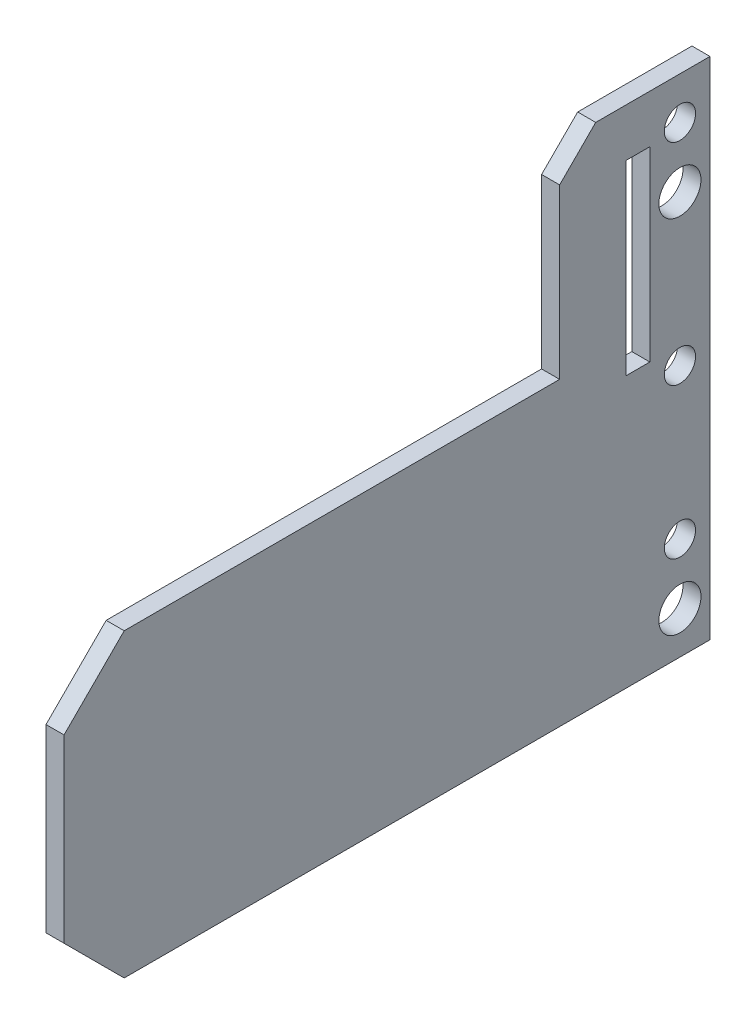
SolidWorks part; units mm, degrees
material "Alliage 1060"
ref_plane "Plan de face" through (0, 0, 0) normal (0, 0, 1) x (1, 0, 0)
ref_plane "Plan de dessus" through (0, 0, 0) normal (0, 1, 0) x (1, 0, 0)
ref_plane "Plan de droite" through (0, 0, 0) normal (1, 0, 0) x (0, 0, -1)
sketch "Esquisse1" plane through (0, 0, 0) normal (1, 0, 0) x (0, 0, -1)
  line L1 (2.5, 21) -> (-51.2, 21)
  line L2 (2.5, 21) -> (2.5, -21)
  line L3 (2.5, -21) -> (-51.2, -21)
  line L4 (-51.2, 21) -> (-51.2, -21)
  line L5 (-6.2, -1.4447) -> (-6.2, -2.9447) construction
  circle A2 centre (0, -17.5) radius 1.75
  circle A3 centre (0, 12.5) radius 1.75
  circle A4 centre (0, 12.5) radius 1.5 construction
  circle A5 centre (0, -17.5) radius 1.5 construction
  dimension "D2" = 3.5
  dimension "D1" = 45
extrude "Extrusion1" add sketch "Esquisse1" along normal blind 1.5
hole_wizard "Fraisage pour vis à tête fraisée M2.51" positions "Esquisse4" profile "Esquisse3" hole size "#0000" standard "Ansi Pouces" end condition through all
sketch "Esquisse4" plane through (1.5, 0, 0) normal (1, 0, 0) x (0, 0, -1)
  circle A0 centre (0, -17.5) radius 1.5 construction
  circle A1 centre (0, 12.5) radius 1.5 construction
  point P0 (0, 17.5)
  point P1 (0, -12.5)
  point P5 (0, 0)
  dimension "D2" = 5
  dimension "D1" = 5
sketch "Esquisse3" plane through (1.5, 17.5, 0) normal (0, 1, 0) x (0, 0, -1)
  line L0 (0, 0) -> (0, 1.5)
  line L1 (0, 1.5) -> (1.3, 1.5)
  line L2 (1.3, 1.5) -> (1.3, 0)
  line L5 (1.3, 0) -> (0, 0)
  line L11 (0, -6.35) -> (0, 107.95) construction
  dimension "Diamètre du perçage jusqu'au prochain" = 2.6
  dimension "Profondeur du perçage jusqu'au prochain" = 1.5
sketch "Esquisse5" plane through (0, 0, 0) normal (-1, 0, 0) x (0, 0, 1)
  line L0 (2.5, -21) -> (2.5, 21) construction
  line L1 (2.5, 17) -> (4.5, 17)
  line L2 (2.5, 17) -> (2.5, 1.5)
  line L3 (2.5, 1.5) -> (4.5, 1.5)
  line L4 (4.5, 17) -> (4.5, 1.5)
  dimension "D1" = 2
  dimension "D2" = 17
  dimension "D3" = 1.5
extrude "Enlèv. mat.-Extru.1" cut sketch "Esquisse5" against normal through all
sketch "Esquisse6" plane through (1.5, 0, 0) normal (1, 0, 0) x (0, 0, -1)
  line L0 (-51.2, 21) -> (-51.2, -1)
  line L1 (-51.2, 21) -> (-51.2, -21) construction
  line L2 (-46.2, 4) -> (-10, 4)
  line L3 (-10, 4) -> (-10, 18)
  line L4 (-10, 18) -> (-7, 21)
  line L5 (2.5, 21) -> (-51.2, 21) construction
  line L6 (-7, 21) -> (-51.2, 21)
  line L7 (-51.2, -21) -> (2.5, -21) construction
  line L8 (-46.2, 4) -> (-51.2, -1)
  line L9 (-51.2, -21) -> (-46.2, -21)
  line L10 (-46.2, -21) -> (-51.2, -16)
  line L11 (-51.2, -16) -> (-51.2, -21)
  dimension "D1" = 45
  dimension "D2" = 10
  dimension "D3" = 25
  dimension "D4" = 3
  dimension "D5" = 5
  dimension "D6" = 5
  dimension "D7" = 5
  dimension "D8" = 5
extrude "Enlèv. mat.-Extru.2" cut sketch "Esquisse6" against normal up to next
